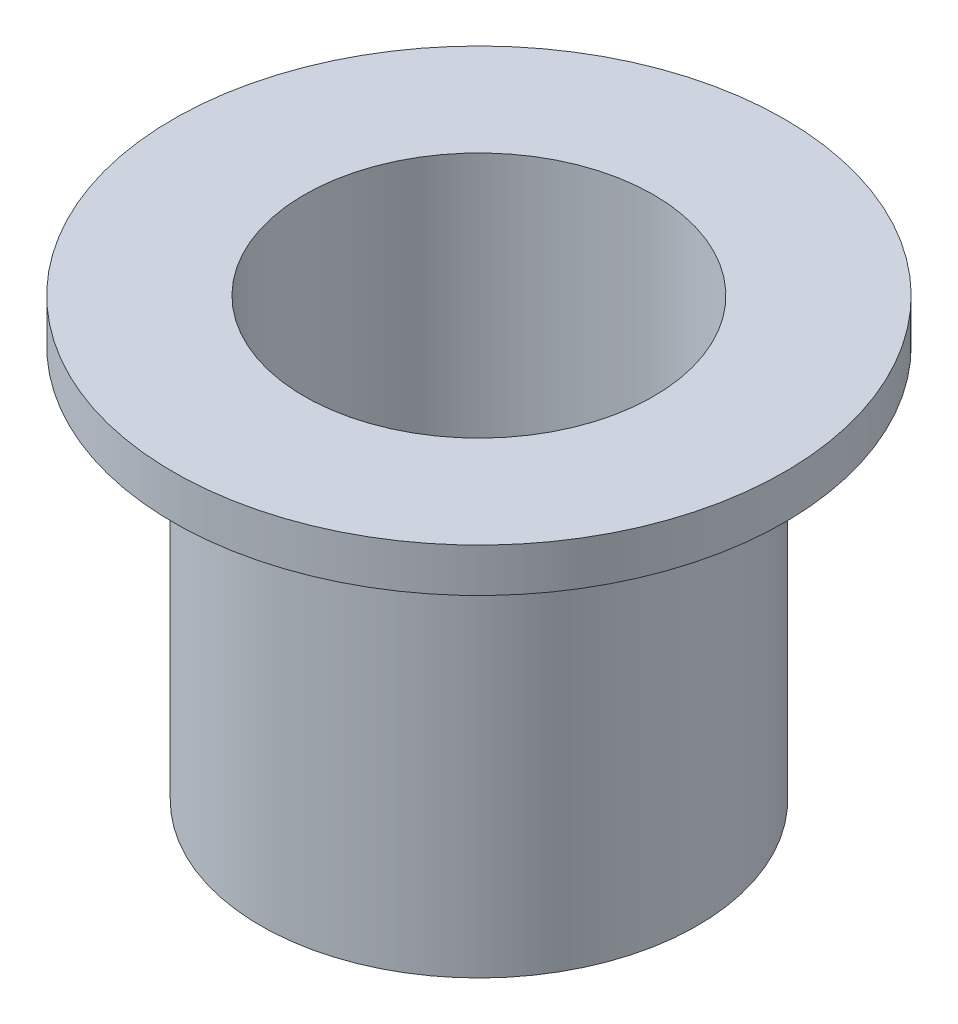
SolidWorks part; units mm, degrees
material "Brass"
ref_plane "Front Plane" through (0, 0, 0) normal (0, 0, 1) x (1, 0, 0)
ref_plane "Top Plane" through (0, 0, 0) normal (0, 1, 0) x (1, 0, 0)
ref_plane "Right Plane" through (0, 0, 0) normal (1, 0, 0) x (0, 0, -1)
sketch "Sketch1" plane through (0, 0, 0) normal (0, 0, 1) x (1, 0, 0)
  line L0 (0, 0) -> (0, 31.0029) construction
  line L1 (-12.7, -2.0544) -> (-12.7, 29.6956)
  line L2 (-12.7, 29.6956) -> (-22.225, 29.6956)
  line L3 (-22.225, 29.6956) -> (-22.225, 26.5206)
  line L4 (-22.225, 26.5206) -> (-15.875, 26.5206)
  line L5 (-15.875, 26.5206) -> (-15.875, -2.0544)
  line L6 (-15.875, -2.0544) -> (-12.7, -2.0544)
  dimension "D1" = 31.75
  dimension "D2" = 12.7
  dimension "D3" = 15.875
  dimension "D4" = 3.175
  dimension "D5" = 9.525
revolve "Revolve1" add sketch "Sketch1" angle 360 about L0
